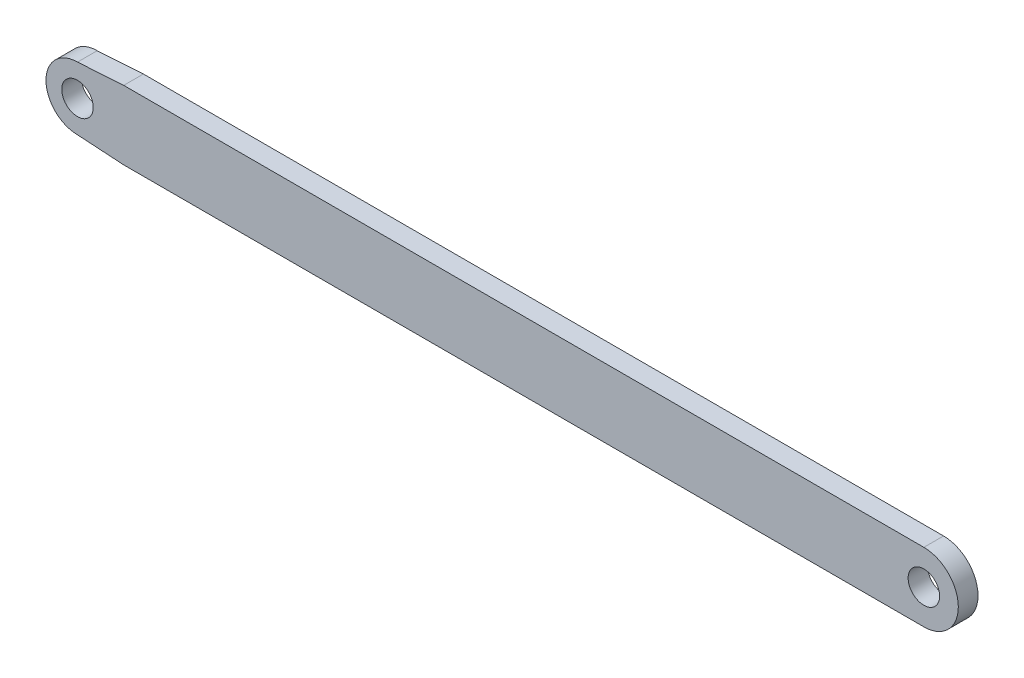
SolidWorks part; units mm, degrees
ref_plane "前视基准面" through (0, 0, 0) normal (0, 0, 1) x (1, 0, 0)
ref_plane "上视基准面" through (0, 0, 0) normal (0, 1, 0) x (1, 0, 0)
ref_plane "右视基准面" through (0, 0, 0) normal (1, 0, 0) x (0, 0, -1)
other "Configuration Table"
sketch "草图3" plane through (0, 0, 0) normal (0, 0, 1) x (1, 0, 0)
  line L0 (203.2592, 8.75) -> (0, 8.75)
  line L1 (0, -8.75) -> (215, -8.75)
  line L2 (0, 8.75) -> (-11.7408, 8)
  line L3 (0, -8.75) -> (-11.7408, -8)
  line L4 (203.2592, 8.75) -> (203.2592, -8.75)
  circle A0 centre (-11.7408, 0) radius 8
  circle A1 centre (203.2592, 0) radius 8.75
  dimension "D1" = 16
  dimension "D2" = 17.5
  dimension "D3" = 215
extrude "凸台-拉伸1" add sketch "草图3" along normal blind 5 contours A1 L0 L2 A0 L3 L1 | A0 | L4 A1 | L4 A1
sketch "草图4" plane through (0, 0, 5) normal (0, 0, 1) x (1, 0, 0)
  circle A0 centre (-11.7408, 0) radius 4
  circle A1 centre (203.2592, 0) radius 4
  dimension "D1" = 8
  dimension "D2" = 8
extrude "切除-拉伸1" cut sketch "草图4" against normal through all
